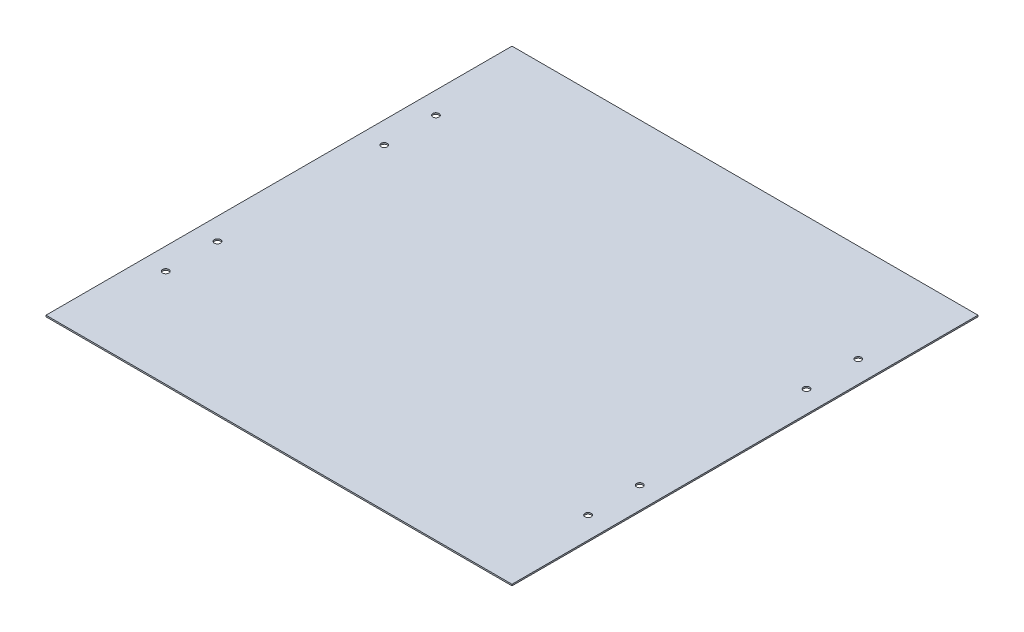
SolidWorks part; units mm, degrees
material "1.4000 (X6Cr13)"
ref_plane "Ebene vorne" through (0, 0, 0) normal (0, 0, 1) x (1, 0, 0)
ref_plane "Ebene oben" through (0, 0, 0) normal (0, 1, 0) x (1, 0, 0)
ref_plane "Ebene rechts" through (0, 0, 0) normal (1, 0, 0) x (0, 0, -1)
sketch "Skizze1" plane through (0, 0, 0) normal (0, 1, 0) x (1, 0, 0)
  line L1 (-160, -160) -> (160, -160)
  line L2 (-160, -160) -> (-160, 160)
  line L3 (-160, 160) -> (160, 160)
  line L4 (160, -160) -> (160, 160)
  line L5 (-160, -160) -> (160, 160) construction
  line L6 (-160, 160) -> (160, -160) construction
  point P0 (0, 0)
extrude "Aufsatz-Linear austragen1" add sketch "Skizze1" along normal blind 1
sketch "Skizze2" plane through (0, 1, 0) normal (0, 1, 0) x (1, 0, 0)
  line L0 (0, 0) -> (0, 160)
  line L1 (160, 160) -> (-160, 160) construction
  line L2 (0, 0) -> (0, -160)
  line L3 (-160, -160) -> (160, -160) construction
  line L4 (0, 0) -> (-160, 0)
  line L5 (-160, 160) -> (-160, -160) construction
  line L6 (0, 0) -> (160, 0)
  line L7 (160, -160) -> (160, 160) construction
  line L8 (145, 0) -> (145, 75)
  line L9 (145, 75) -> (145, 92.75)
  line L10 (145, 75) -> (-160, 75)
  line L11 (145, 92.75) -> (160, 92.75)
  circle A0 centre (145, 92.75) radius 2.15
  circle A1 centre (145, 57.25) radius 2.15
  circle A2 centre (145, -57.25) radius 2.15
  circle A3 centre (145, -92.75) radius 2.15
  circle A4 centre (-145, 92.75) radius 2.15
  circle A5 centre (-145, 57.25) radius 2.15
  circle A6 centre (-145, -92.75) radius 2.15
  circle A7 centre (-145, -57.25) radius 2.15
  dimension "D1" = 4.3
extrude "Schnitt-Linear austragen1" cut sketch "Skizze2" against normal blind 2 contours A2 | A3 | A0 | A1 | A4 | A5 | A6 | A7
equation "\"M4_mutter\"= 7.4mm"
equation "\"M4_loch\"= 4.3mm"
equation "\"M8_loch\"= 8.4mm"
equation "\"D1@Skizze2\"=\"M4_loch\""
